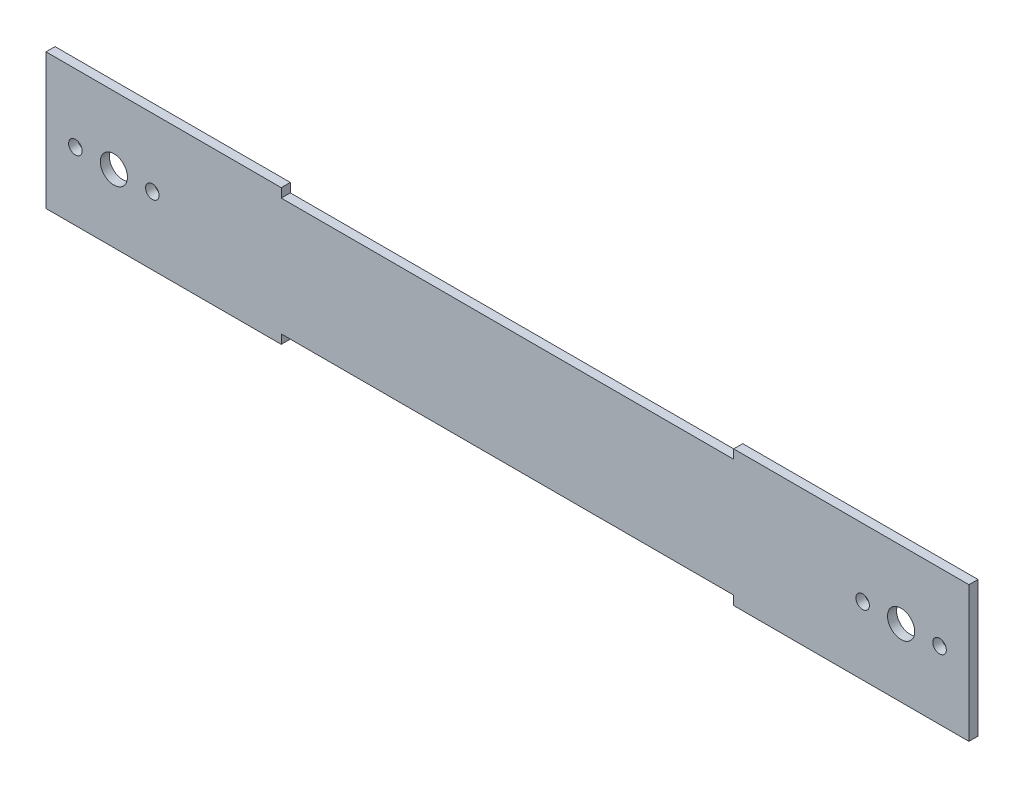
SolidWorks part; units mm, degrees
ref_plane "Front Plane" through (0, 0, 0) normal (0, 0, 1) x (1, 0, 0)
ref_plane "Top Plane" through (0, 0, 0) normal (0, 1, 0) x (1, 0, 0)
ref_plane "Right Plane" through (0, 0, 0) normal (1, 0, 0) x (0, 0, -1)
sketch "Sketch1" plane through (0, 0, 0) normal (0, 0, 1) x (1, 0, 0)
  line L2 (0, -15) -> (0, 0)
  line L3 (0, -15) -> (52, -15)
  line L4 (52, -15) -> (52, -13)
  line L5 (52, -13) -> (152, -13)
  line L6 (152, -13) -> (152, -15)
  line L7 (152, -15) -> (204, -15)
  line L8 (0, 0) -> (204, 0)
  line L9 (204, 0) -> (204, -15)
  dimension "D1" = 2
  dimension "D2" = 100
  dimension "D3" = 52
  dimension "D4" = 52
extrude "Boss-Extrude1" add sketch "Sketch1" along normal blind 2
mirror "Mirror2" about plane through (0, 0, 2) normal (0, -1, 0) of "Boss-Extrude1"
sketch "Sketch2" plane through (0, 0, 2) normal (0, 0, 1) x (1, 0, 0)
  line L0 (204, -15) -> (204, 15) construction
  circle A0 centre (6.5, 0) radius 1.5
  circle A1 centre (15, 0) radius 3
  circle A2 centre (23.5, 0) radius 1.5
  circle A3 centre (180.5, 0) radius 1.5
  circle A4 centre (189, 0) radius 3
  circle A5 centre (197.5, 0) radius 1.5
  point P12 (0, 0)
  point P14 (0, 0)
  point P15 (53.6928, 17.5663)
  dimension "D2" = 3
  dimension "D3" = 3
  dimension "D6" = 6
  dimension "D7" = 3
  dimension "D8" = 6
  dimension "D9" = 3
  dimension "D1" = 6.5
  dimension "D4" = 8.5
  dimension "D5" = 8.5
  dimension "D10" = 6.5
  dimension "D11" = 8.5
  dimension "D12" = 8.5
extrude "Cut-Extrude1" cut sketch "Sketch2" against normal blind 2
